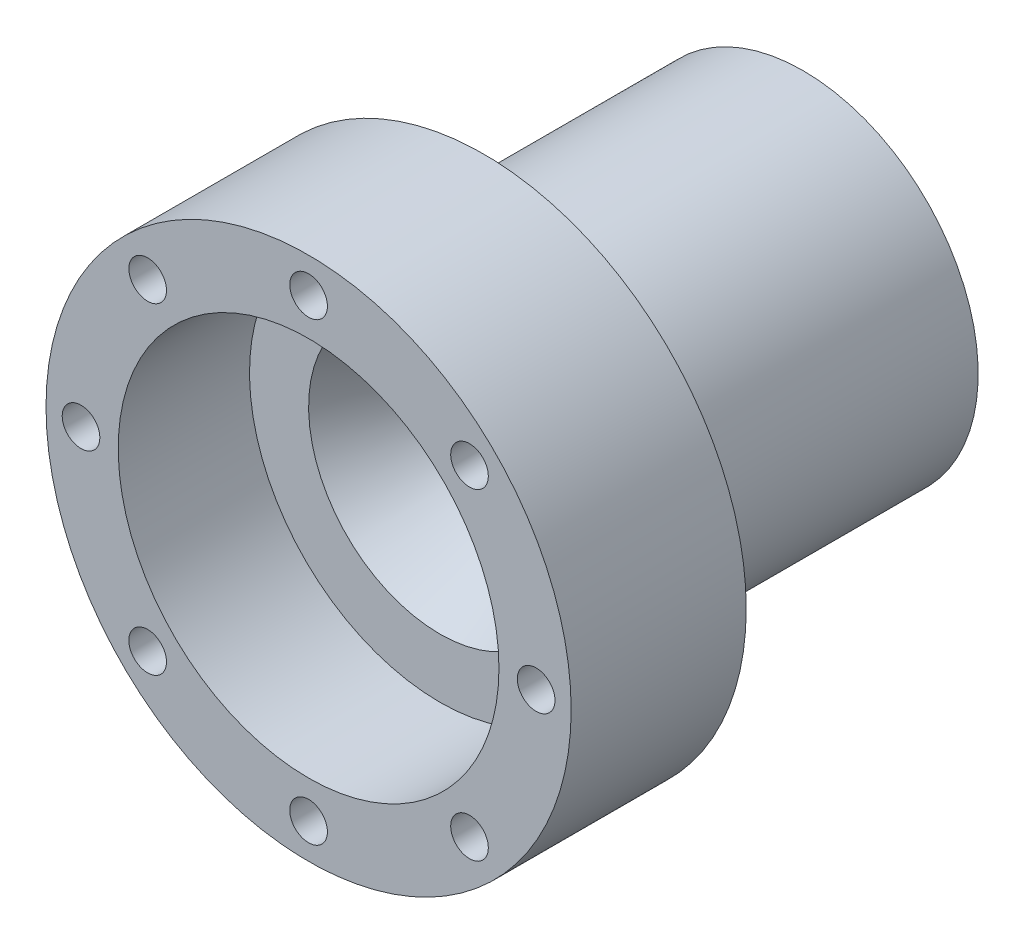
SolidWorks part; units mm, degrees
ref_plane "Front Plane" through (0, 0, 0) normal (0, 0, 1) x (1, 0, 0)
ref_plane "Top Plane" through (0, 0, 0) normal (0, 1, 0) x (1, 0, 0)
ref_plane "Right Plane" through (0, 0, 0) normal (1, 0, 0) x (0, 0, -1)
sketch "Sketch2" plane through (0, 0, 0) normal (1, 0, 0) x (0, 0, -1)
  line L1 (21.3287, 20) -> (21.3287, 10.285)
  line L2 (21.3287, 10.285) -> (0, 4.57)
  line L4 (-20.1713, 15) -> (-20.1713, 20)
  line L6 (-20.1713, 20) -> (21.3287, 20)
  line L7 (0, 0) -> (60, 0) construction
  line L8 (0, 0) -> (-60, 0) construction
  line L9 (-20.1713, 15) -> (-2.106, 4.57)
  line L10 (-2.106, 4.57) -> (0, 4.57)
  dimension "D1" = 4.57
  dimension "D2" = 120
  dimension "D3" = 60
  dimension "D4" = 10.285
  dimension "D5" = 20
  dimension "D6" = 105
  dimension "D7" = 41.5
  dimension "D8" = 15
  dimension "D9" = 120
revolve "Revolve1" add sketch "Sketch2" angle 360 about L8
sketch "Sketch4" plane through (0, 0, 20.1713) normal (0, 0, 1) x (1, 0, 0)
  circle A0 centre (0, 0) radius 30
  circle A1 centre (0, 0) radius 20 construction
  circle A2 centre (0, 0) radius 20
  dimension "D1" = 60
extrude "Boss-Extrude1" add sketch "Sketch4" against normal blind 5
sketch "Sketch5" plane through (0, 0, 20.1713) normal (0, 0, 1) x (1, 0, 0)
  circle A0 centre (0, 0) radius 21.75
  circle A1 centre (0, 0) radius 30 construction
  circle A2 centre (0, 0) radius 30
  dimension "D1" = 43.5
extrude "Boss-Extrude2" add sketch "Sketch5" along normal blind 15
hole_wizard "M4 Clearance Hole1" positions "Sketch6" profile "Sketch8" hole size "M4" standard "ISO" end condition up to next
sketch "Sketch6" plane through (0, 0, 15.1713) normal (0, 0, -1) x (-1, 0, 0)
  point P0 (0, 26)
  dimension "D1" = 26
sketch "Sketch8" plane through (0, 26, 15.1713) normal (1, 0, 0) x (0, 1, 0)
  line L0 (0, 0) -> (0, 20)
  line L1 (0, 20) -> (2.15, 20)
  line L2 (2.15, 20) -> (2.15, 0)
  line L5 (2.15, 0) -> (0, 0)
  line L11 (0, -6.35) -> (0, 107.95) construction
  dimension "Thru Hole Dia." = 4.3
  dimension "Thru Hole Depth" = 20
pattern_circular "CirPattern1" count 8 over 360 about axis through (0, 0, 0) along (0, 0, 1) of "M4 Clearance Hole1"
